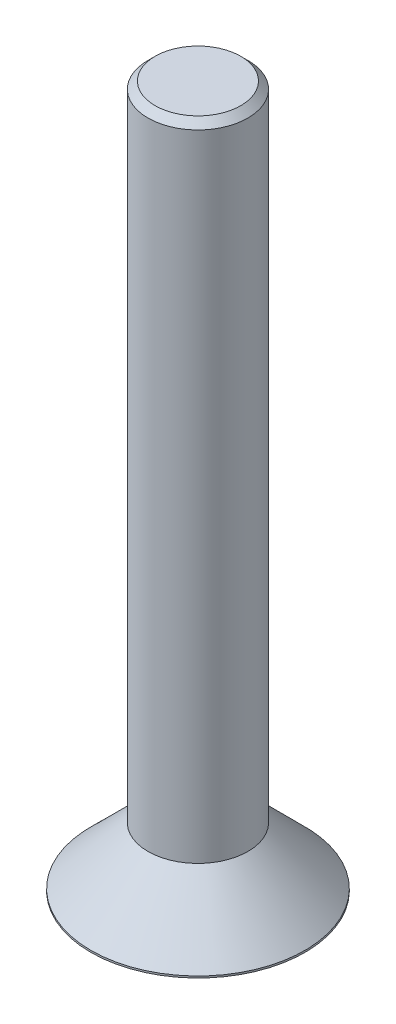
SolidWorks part; units mm, degrees
ref_plane "前视基准面" through (0, 0, 0) normal (0, 0, 1) x (1, 0, 0)
ref_plane "上视基准面" through (0, 0, 0) normal (0, 1, 0) x (1, 0, 0)
ref_plane "右视基准面" through (0, 0, 0) normal (1, 0, 0) x (0, 0, -1)
sketch "草图1" plane through (0, 0, 0) normal (0, 1, 0) x (1, 0, 0)
  circle A0 centre (0, 0) radius 3
  dimension "D1" = 6
extrude "凸台-拉伸1" add sketch "草图1" along normal blind 1.65
chamfer "倒角1" distance 1.6 angle 45 1 edges at (0, 1.65, 3)
sketch "草图2" plane through (0, 0, 0) normal (0, -1, 0) x (1, 0, 0)
  line L1 (1, -0.5774) -> (1, 0.5774)
  line L2 (1, 0.5774) -> (0, 1.1547)
  line L3 (0, 1.1547) -> (-1, 0.5774)
  line L4 (-1, 0.5774) -> (-1, -0.5774)
  line L5 (-1, -0.5774) -> (0, -1.1547)
  line L6 (0, -1.1547) -> (1, -0.5774)
  circle A0 centre (0, 0) radius 1 construction
  dimension "D1" = 2
extrude "切除-拉伸1" cut sketch "草图2" against normal blind 0.95
sketch "草图3" plane through (0, 1.65, 0) normal (0, 1, 0) x (1, 0, 0)
  circle A0 centre (0, 0) radius 1.4
  dimension "D1" = 2.8
extrude "凸台-拉伸2" add sketch "草图3" along normal blind 18
chamfer "倒角2" distance 0.2 angle 45 1 edges at (0, 19.65, 1.4)
